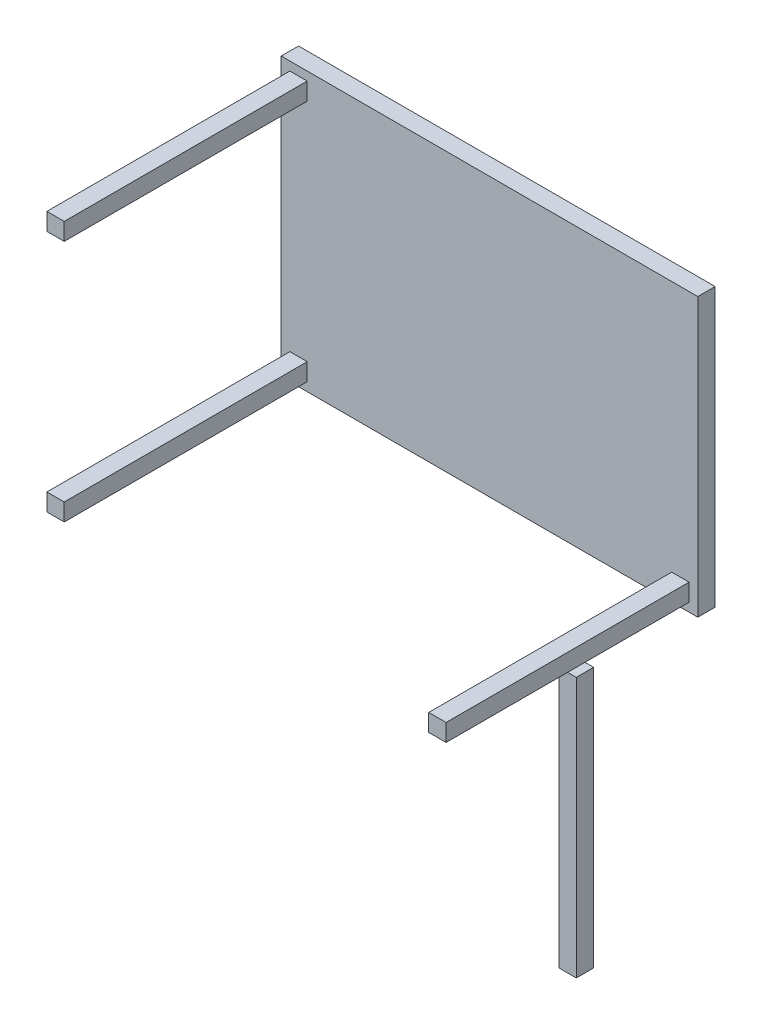
SolidWorks part; units mm, degrees
ref_plane "前视基准面" through (0, 0, 0) normal (0, 0, 1) x (1, 0, 0)
ref_plane "上视基准面" through (0, 0, 0) normal (0, 1, 0) x (1, 0, 0)
ref_plane "右视基准面" through (0, 0, 0) normal (1, 0, 0) x (0, 0, -1)
other "Configuration Table"
sketch "草图1" plane through (0, 0, 0) normal (0, 0, 1) x (1, 0, 0)
  line L1 (-600, -400) -> (600, -400)
  line L2 (-600, -400) -> (-600, 400)
  line L3 (-600, 400) -> (600, 400)
  line L4 (600, -400) -> (600, 400)
  line L5 (-600, -400) -> (600, 400) construction
  line L6 (-600, 400) -> (600, -400) construction
  point P0 (0, 0)
extrude "凸台-拉伸1" add sketch "草图1" along normal blind 50
sketch "草图2" plane through (0, -400, 0) normal (0, -1, 0) x (1, 0, 0)
  line L1 (525, 325) -> (575, 325)
  line L2 (525, 325) -> (525, 375)
  line L3 (525, 375) -> (575, 375)
  line L4 (575, 325) -> (575, 375)
  line L5 (525, 325) -> (575, 375) construction
  line L6 (525, 375) -> (575, 325) construction
  point P0 (550, 350)
extrude "凸台-拉伸2" add sketch "草图2" along normal blind 750
sketch "草图3" plane through (0, 0, 0) normal (0, 0, 1) x (1, 0, 0)
  line L1 (-575, 325) -> (-525, 325)
  line L2 (-575, 325) -> (-575, 375)
  line L3 (-575, 375) -> (-525, 375)
  line L4 (-525, 325) -> (-525, 375)
  line L5 (-575, 325) -> (-525, 375) construction
  line L6 (-575, 375) -> (-525, 325) construction
  point P0 (-550, 350)
extrude "凸台-拉伸3" add sketch "草图3" along normal blind 750
sketch "草图4" plane through (0, 0, 0) normal (0, 0, 1) x (1, 0, 0)
  line L1 (525, -375) -> (575, -375)
  line L2 (525, -375) -> (525, -325)
  line L3 (525, -325) -> (575, -325)
  line L4 (575, -375) -> (575, -325)
  line L5 (525, -375) -> (575, -325) construction
  line L6 (525, -325) -> (575, -375) construction
  point P0 (550, -350)
extrude "凸台-拉伸4" add sketch "草图4" along normal blind 750
sketch "草图5" plane through (0, 0, 0) normal (0, 0, 1) x (1, 0, 0)
  line L1 (-575, -375) -> (-525, -375)
  line L2 (-575, -375) -> (-575, -325)
  line L3 (-575, -325) -> (-525, -325)
  line L4 (-525, -375) -> (-525, -325)
  line L5 (-575, -375) -> (-525, -325) construction
  line L6 (-575, -325) -> (-525, -375) construction
  point P0 (-550, -350)
extrude "凸台-拉伸5" add sketch "草图5" along normal blind 750
